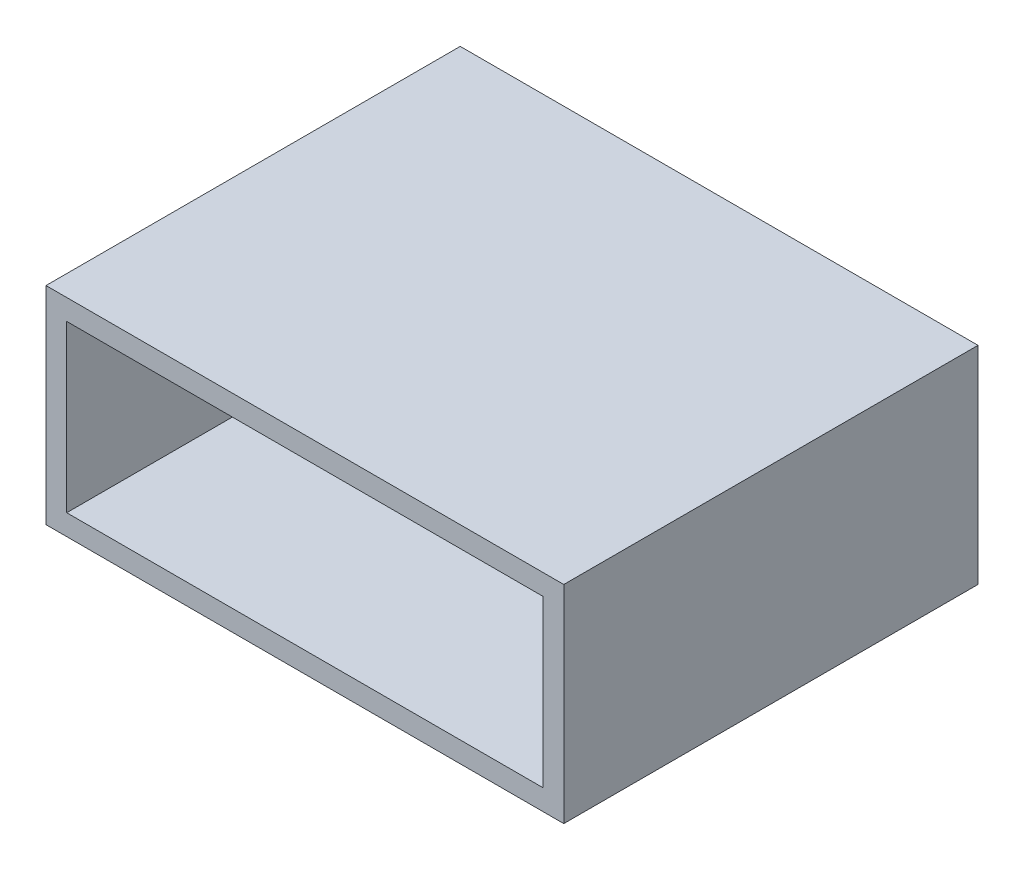
SolidWorks part; units mm, degrees
ref_plane "Front Plane" through (0, 0, 0) normal (0, 0, 1) x (1, 0, 0)
ref_plane "Top Plane" through (0, 0, 0) normal (0, 1, 0) x (1, 0, 0)
ref_plane "Right Plane" through (0, 0, 0) normal (1, 0, 0) x (0, 0, -1)
sketch "Sketch1" plane through (0, 0, 0) normal (0, 0, 1) x (1, 0, 0)
  line L1 (0, 0) -> (127, 0)
  line L2 (0, 0) -> (0, -50.8)
  line L3 (0, -50.8) -> (127, -50.8)
  line L4 (127, 0) -> (127, -50.8)
  dimension "D1" = 50.8
  dimension "D2" = 127
extrude "Boss-Extrude1" add sketch "Sketch1" along normal blind 101.6
sketch "Sketch2" plane through (0, 0, 0) normal (0, 0, -1) x (-1, 0, 0)
  line L0 (-127, -50.8) -> (-127, 0) construction
  line L1 (-121.92, -5.08) -> (-5.08, -5.08)
  line L2 (-121.92, -5.08) -> (-121.92, -45.72)
  line L3 (-121.92, -45.72) -> (-5.08, -45.72)
  line L4 (-5.08, -5.08) -> (-5.08, -45.72)
  line L5 (-127, 0) -> (0, 0) construction
  line L6 (0, -50.8) -> (-127, -50.8) construction
  line L7 (0, 0) -> (0, -50.8) construction
  dimension "D1" = 5.08
  dimension "D2" = 5.08
  dimension "D3" = 5.08
  dimension "D4" = 5.08
extrude "Cut-Extrude1" cut sketch "Sketch2" against normal up to next
